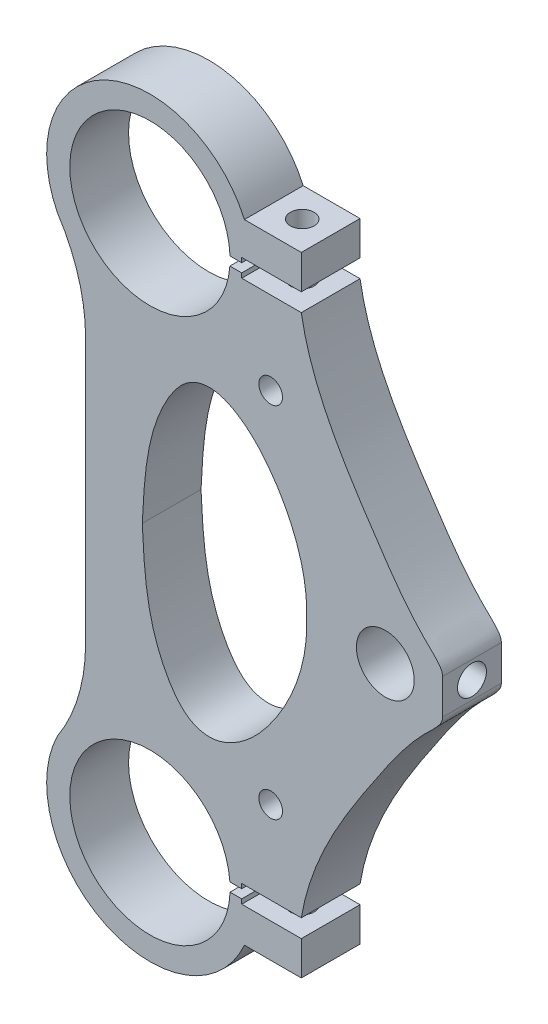
SolidWorks part; units mm, degrees
ref_plane "Piano frontale" through (0, 0, 0) normal (0, 0, 1) x (1, 0, 0)
ref_plane "Piano superiore" through (0, 0, 0) normal (0, 1, 0) x (1, 0, 0)
ref_plane "Piano destro" through (0, 0, 0) normal (1, 0, 0) x (0, 0, -1)
sketch "Schizzo1" plane through (0, 0, 0) normal (0, 0, 1) x (1, 0, 0)
  line L0 (44.652, 38.3399) -> (-8.3277, 38.3399) construction
  line L1 (10.783, 26.8988) -> (10.783, 49.781)
  line L2 (24.2823, 62.1538) -> (24.2823, 62.5538)
  line L3 (24.2823, 62.5538) -> (29.4323, 62.5538)
  line L4 (29.4323, 62.5538) -> (29.4323, 65.5038)
  line L5 (29.4323, 65.5038) -> (24.5149, 65.5038)
  line L6 (24.2823, 62.1538) -> (23.2712, 62.1538)
  line L7 (23.258, 61.3982) -> (24.2823, 61.3982)
  line L8 (24.2823, 61.3982) -> (24.2823, 60.9982)
  line L9 (24.2823, 60.9982) -> (29.4323, 60.9982)
  line L12 (41.648, 39.8619) -> (41.648, 36.8178)
  line L15 (24.2823, 15.6815) -> (29.4323, 15.6815)
  line L16 (24.2823, 15.2815) -> (24.2823, 15.6815)
  line L17 (23.258, 15.2815) -> (24.2823, 15.2815)
  line L18 (24.2823, 14.5259) -> (23.2712, 14.5259)
  line L19 (29.4323, 11.1759) -> (24.5149, 11.1759)
  line L20 (29.4323, 14.1259) -> (29.4323, 11.1759)
  line L21 (24.2823, 14.1259) -> (29.4323, 14.1259)
  line L22 (24.2823, 14.5259) -> (24.2823, 14.1259)
  line L23 (28.3915, 50.0978) -> (30.3532, 44.6715) construction
  line L24 (28.3915, 26.5819) -> (30.3532, 32.0083) construction
  line L25 (37.083, 51.6399) -> (37.083, 55.6399) construction
  circle A0 centre (36.6966, 38.3399) radius 2.5
  circle A1 centre (16.3459, 61.8965) radius 6.93
  arc A2 (24.5149, 65.5038) -> (9.0355, 56.7679) centre (16.3459, 61.8965) ccw
  arc A3 (10.783, 49.781) -> (8.3437, 57.9329) centre (-4.0586, 49.781) ccw
  circle A4 centre (16.3459, 61.8965) radius 8.93 construction
  arc A5 (10.783, 26.8988) -> (8.3437, 18.7468) centre (-4.0586, 26.8988) cw
  arc A6 (24.5149, 11.1759) -> (9.0355, 19.9118) centre (16.3459, 14.7832) cw
  circle A7 centre (16.3459, 14.7832) radius 6.93
  circle A8 centre (26.783, 53.8399) radius 1.1499 construction
  circle A9 centre (37.083, 55.6399) radius 1.1192 construction
  circle A10 centre (37.083, 51.6399) radius 1.0752 construction
  circle A11 centre (26.783, 22.8399) radius 1.1499 construction
  circle A12 centre (37.083, 21.0399) radius 1.1192 construction
  circle A13 centre (37.083, 25.0399) radius 1.0752 construction
  spline S0 degree 3 poles (29.4323, 60.9982) (30.2885, 55.911) (33.9897, 50.137) (38.1293, 44.0517) (40.0263, 41.927) (41.1108, 40.9545) (41.648, 40.2248) (41.648, 39.8619) knots 0 0 0 0 0.614811 0.820092 0.896457 0.95873 1 1 1 1
  spline S2 degree 3 poles (29.4323, 15.6815) (30.2885, 20.7687) (33.9897, 26.5427) (38.1293, 32.6281) (40.0263, 34.7528) (41.1108, 35.7253) (41.648, 36.4549) (41.648, 36.8178) knots 0 0 0 0 0.614811 0.820092 0.896457 0.95873 1 1 1 1
  spline S4 degree 3 poles (15.6826, 38.3399) (15.8621, 41.8407) (16.077, 46.4843) (19.436, 51.1792) (22.0032, 51.5591) (24.463, 50.5183) (27.0177, 47.7705) (29.3099, 43.5608) (29.9723, 40.1777) (29.8861, 38.3399) knots 0 0 0 0 0.321955 0.444159 0.483908 0.555795 0.683183 0.828712 1 1 1 1
  spline S5 degree 3 poles (15.6826, 38.3399) (15.8621, 34.839) (16.077, 30.1954) (19.436, 25.5005) (22.0032, 25.1207) (24.463, 26.1614) (27.0177, 28.9092) (29.3099, 33.119) (29.9723, 36.5021) (29.8861, 38.3399) knots 0 0 0 0 0.321955 0.444159 0.483908 0.555795 0.683183 0.828712 1 1 1 1
  spline S6 degree 3 poles (28.3915, 50.0978) (27.8594, 50.7048) (28.4692, 52.3186) (30.0286, 52.0526) (31.1131, 51.4818) (32.3557, 51.1014) (33.193, 50.1474) (33.7119, 49.1497) (34.5378, 48.0878) (34.6681, 46.8838) (34.3882, 45.7037) (33.6402, 44.7109) (33.0671, 43.5351) (32.0346, 43.17) (31.284, 43.3773) (30.8794, 43.6857) (30.6816, 43.8562) (30.3532, 44.6715) knots 0 0 0 0 0.13684 0.17515 0.257072 0.352961 0.390177 0.472943 0.54801 0.617627 0.673801 0.753613 0.832487 0.887817 0.933329 0.944548 1 1 1 1 construction
  spline S7 degree 3 poles (28.3915, 26.5819) (27.8594, 25.9749) (28.4692, 24.3611) (30.0286, 24.6271) (31.1131, 25.1979) (32.3557, 25.5784) (33.193, 26.5324) (33.7119, 27.53) (34.5378, 28.592) (34.6681, 29.7959) (34.3882, 30.9761) (33.6402, 31.9689) (33.0671, 33.1447) (32.0346, 33.5098) (31.284, 33.3025) (30.8794, 32.994) (30.6816, 32.8235) (30.3532, 32.0083) knots 0 0 0 0 0.13684 0.17515 0.257072 0.352961 0.390177 0.472943 0.54801 0.617627 0.673801 0.753613 0.832487 0.887817 0.933329 0.944548 1 1 1 1 construction
  point P72 (41.648, 38.3399)
  point P81 (10.783, 38.3399)
  dimension "D1" = 5
  dimension "D2" = 13.86
  dimension "D3" = 2.95
  dimension "D4" = 0.4
  dimension "D5" = 5.15
  dimension "D7" = 4
  dimension "D8" = 15.5
  dimension "D9" = 16
  dimension "D10" = 26.3
  dimension "D11" = 13.3
  dimension "D6" = 2
extrude "Estrusione-Estrusione1" add sketch "Schizzo1" along normal blind 5.08
hole_wizard "Foro filettato M2.5x0.45-1" positions "Schizzo4" profile "Schizzo3" tap size "M2.5x0.45" standard "Ansi Metric" end condition through all
sketch "Schizzo4" plane through (0, 0, 5.08) normal (0, 0, 1) x (1, 0, 0)
  point P6 (26.783, 22.8399)
  point P9 (26.783, 53.8399)
sketch "Schizzo3" plane through (26.783, 22.8399, 5.08) normal (1, 0, 0) x (0, -1, 0)
  line L0 (0, 0) -> (0, 5.08)
  line L1 (0, 5.08) -> (1.025, 5.08)
  line L2 (1.025, 5.08) -> (1.025, 0)
  line L5 (1.025, 0) -> (0, 0)
  line L11 (0, -6.35) -> (0, 107.95) construction
  dimension "Thread Major Dia." = 2.05
  dimension "Thru Tap Drill Depth" = 5.08
hole_wizard "Foro filettato M3x0.5-1" positions "Schizzo6" profile "Schizzo5" tap size "M3x0.5" standard "Ansi Metric"
sketch "Schizzo6" plane through (41.648, 0, 0) normal (1, 0, 0) x (0, 0, -1)
  line L0 (-5.08, 39.8619) -> (0, 36.8178) construction
  point P0 (-2.54, 38.3399)
  point P15 (-2.54, 38.3399)
sketch "Schizzo5" plane through (41.648, 38.3399, 2.54) normal (0, 1, 0) x (0, 0, -1)
  line L0 (0, 0) -> (0, 2.4514)
  line L1 (0, 2.4514) -> (1.25, 2.4514)
  line L2 (1.25, 2.4514) -> (1.25, 0)
  line L5 (1.25, 0) -> (0, 0)
  line L11 (0, -6.35) -> (0, 107.95) construction
  dimension "Thread Major Dia." = 2.5
  dimension "Thru Tap Drill Depth" = 2.4514
hole_wizard "Foro filettato M2.5x0.45-2" positions "Schizzo8" profile "Schizzo7" tap size "M2.5x0.45" standard "Ansi Metric"
sketch "Schizzo8" plane through (0, 65.5038, 0) normal (0, 1, 0) x (1, 0, 0)
  line L0 (29.4323, 0) -> (24.5149, 0) construction
  line L1 (29.4323, -5.08) -> (29.4323, 0) construction
  point P0 (26.9736, -2.54)
  point P6 (26.9736, 0)
  point P10 (29.4323, -2.54)
sketch "Schizzo7" plane through (26.9736, 65.5038, 2.54) normal (1, 0, 0) x (0, 0, 1)
  line L0 (0, 0) -> (0, 10.6159)
  line L1 (0, 10.6159) -> (1.025, 10)
  line L2 (1.025, 10) -> (1.025, 0)
  line L5 (1.025, 0) -> (0, 0)
  line L10 (0, 10.6159) -> (-1.025, 10) construction
  line L11 (0, -6.35) -> (0, 107.95) construction
  dimension "Tap Drill Dia." = 2.05
  dimension "Tap Drill Depth" = 10
  dimension "Drill Angle" = 118
ref_plane "Piano1" through (0, 38.3399, 0) normal (0, 1, 0) x (1, 0, 0)
mirror "Specchia1" about plane through (0, 38.3399, 0) normal (0, 1, 0) of "Foro filettato M2.5x0.45-2"
